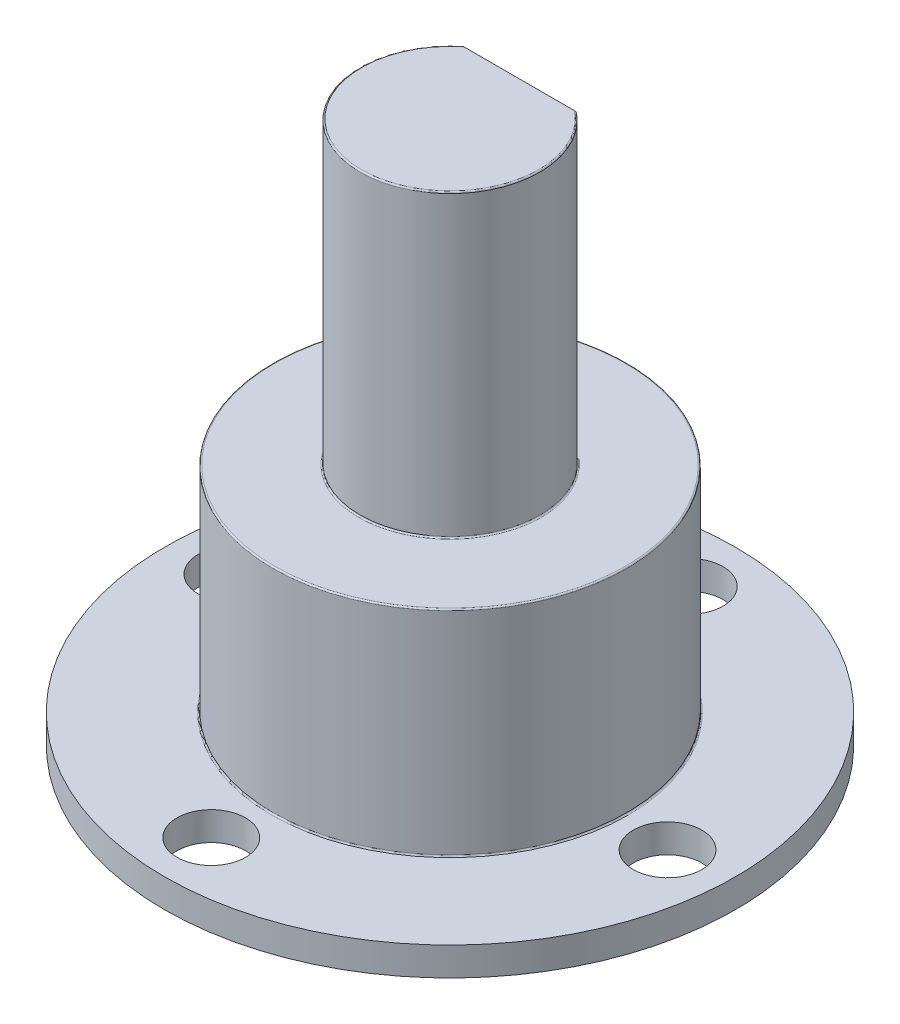
SolidWorks part; units mm, degrees
material "ABS"
ref_plane "Plan de face" through (0, 0, 0) normal (0, 0, 1) x (1, 0, 0)
ref_plane "Plan de dessus" through (0, 0, 0) normal (0, 1, 0) x (1, 0, 0)
ref_plane "Plan de droite" through (0, 0, 0) normal (1, 0, 0) x (0, 0, -1)
sketch "Esquisse2" plane through (0, 0, 0) normal (0, 0, 1) x (1, 0, 0)
  line L0 (0, 19) -> (3.15, 19)
  line L3 (6.2, 3) -> (6.2, 1)
  line L4 (6.2, 1) -> (10, 1)
  line L5 (10, 1) -> (10, 0)
  line L6 (10, 0) -> (0, 0)
  line L9 (0, 0) -> (0, 19)
  line L11 (3.15, 19) -> (3.15, 8.5)
  line L12 (3.15, 8.5) -> (6.2, 8.5)
  line L13 (6.2, 3) -> (6.2, 8.5)
  point P2 (1.575, 19)
  point P3 (0, 0)
  point P8 (0, -0.2372)
  point P10 (0, 0)
  point P12 (0, 0.1836)
  dimension "D1" = 10
  dimension "D2" = 19
  dimension "D3" = 0
  dimension "D4" = 1
  dimension "D5" = 6.2
  dimension "D6" = 2
  dimension "D7" = 8.5
  dimension "D9" = 3.15
  dimension "D10" = 0
revolve "Révolution2" add sketch "Esquisse2" angle 360 about L9
sketch "Esquisse3" plane through (0, 19, 0) normal (0, 1, 0) x (1, 0, 0)
  line L1 (-3.6413, 2.4219) -> (2.9365, 2.4219)
  line L2 (-3.6413, 2.4219) -> (-3.6413, 3.808)
  line L3 (-3.6413, 3.808) -> (2.9365, 3.808)
  line L4 (2.9365, 2.4219) -> (2.9365, 3.808)
  dimension "D1" = 6.5779
extrude "Enlèv. mat.-Extru.1" cut sketch "Esquisse3" against normal up to surface (10.5 mm away) contours L4 L3 L2 L1 up to face at (0, 8.5, -3.15)
hole_wizard "Dégagement M21" positions "Esquisse4" profile "Esquisse5" hole size "M2" standard "Ansi Metric" end condition up to next
sketch "Esquisse4" plane through (0, 1, 0) normal (0, 1, 0) x (1, 0, 0)
  circle A0 centre (0, 0) radius 8 construction
  point P0 (0.3713, 7.9914)
  dimension "D1" = 16
sketch "Esquisse5" plane through (0.3713, 1, -7.9914) normal (1, 0, 0) x (0, 0, 1)
  line L0 (0, 0) -> (0, 1.001)
  line L1 (0, 1.001) -> (1.2, 1.001)
  line L2 (1.2, 1.001) -> (1.2, 0)
  line L5 (1.2, 0) -> (0, 0)
  line L11 (0, -6.35) -> (0, 107.95) construction
  dimension "Diamètre du perçage jusqu'au prochain" = 2.4
  dimension "Profondeur du perçage jusqu'au prochain" = 1.001
pattern_circular "Répétition circulaire1" count 4 over 360 about axis through (0, 0, 0) along (0, 1, 0) of "Dégagement M21"
fillet "Congé1" radius 0.05 4 edges at (0, 8.5, 3.15) (0, 8.5, -6.2) (0, 1, -6.2) (0, 19, 3.15)
